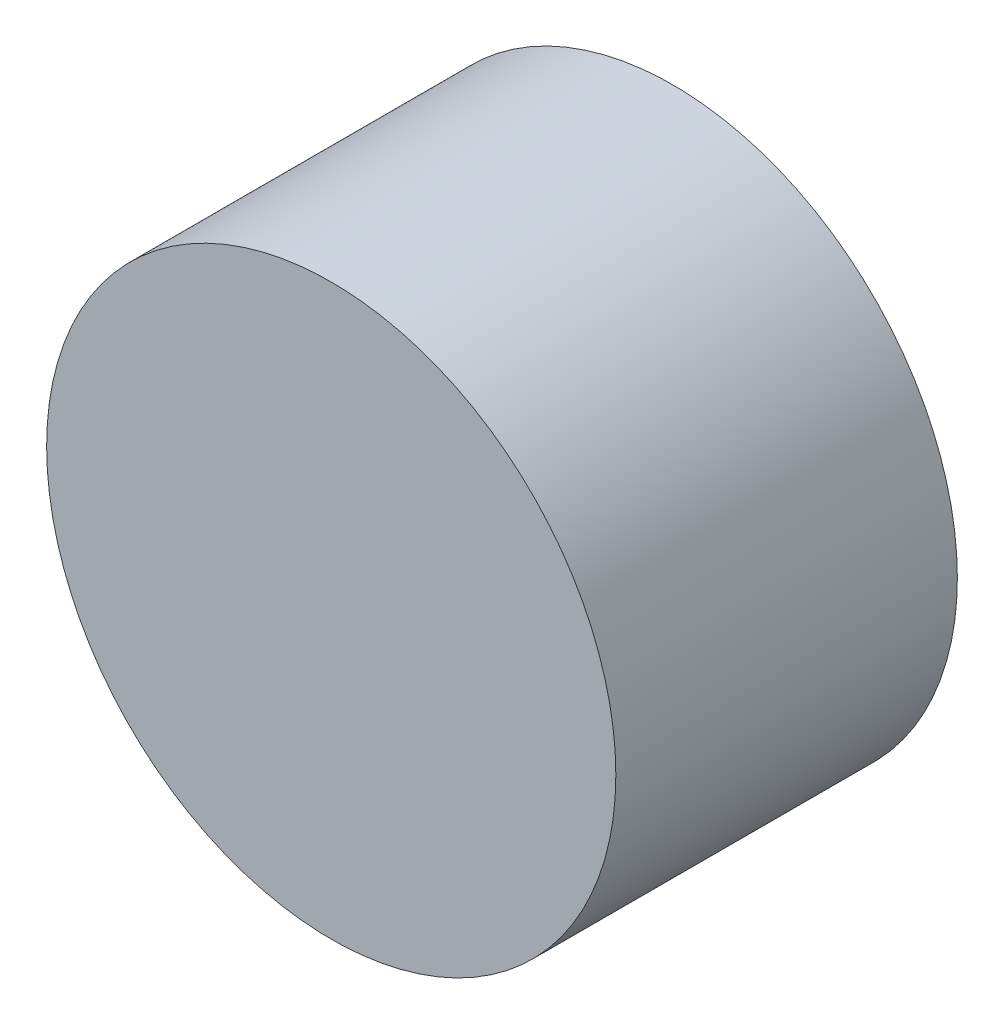
SolidWorks part; units mm, degrees
ref_plane "Front Plane" through (0, 0, 0) normal (0, 0, 1) x (1, 0, 0)
ref_plane "Top Plane" through (0, 0, 0) normal (0, 1, 0) x (1, 0, 0)
ref_plane "Right Plane" through (0, 0, 0) normal (1, 0, 0) x (0, 0, -1)
sketch "Sketch1" plane through (0, 0, 0) normal (0, 0, 1) x (1, 0, 0)
  circle A0 centre (0, 0) radius 5
extrude "Boss-Extrude1" add sketch "Sketch1" along normal blind 6
